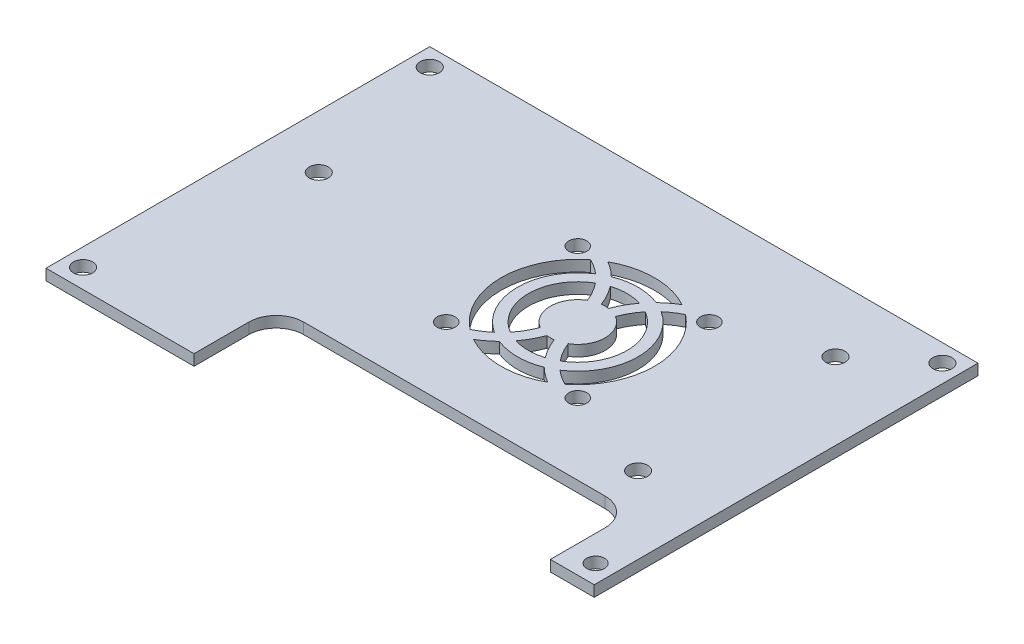
SolidWorks part; units mm, degrees
ref_plane "Front Plane" through (0, 0, 0) normal (0, 0, 1) x (1, 0, 0)
ref_plane "Top Plane" through (0, 0, 0) normal (0, 1, 0) x (1, 0, 0)
ref_plane "Right Plane" through (0, 0, 0) normal (1, 0, 0) x (0, 0, -1)
sketch "Sketch1" plane through (0, 0, 0) normal (0, 1, 0) x (1, 0, 0)
  line L0 (0, 35) -> (0, -35) construction
  line L1 (-50, 35) -> (50, 35)
  line L2 (-50, 35) -> (-50, -35)
  line L3 (-50, -35) -> (50, -35)
  line L4 (50, 35) -> (50, -35)
  line L5 (-46.75, -31.5) -> (46.75, -31.5) construction
  line L6 (7, 20) -> (7, -10) construction
  line L7 (-4, 20) -> (18, 20) construction
  line L8 (-8, 16) -> (-8, -6) construction
  line L9 (-4, -10) -> (18, -10) construction
  line L10 (22, 16) -> (22, -6) construction
  line L11 (-8, 5) -> (22, 5) construction
  circle A0 centre (-46.75, 31.75) radius 1.75
  circle A1 centre (46.75, 31.75) radius 1.75
  circle A2 centre (-46.75, -31.5) radius 1.75
  circle A3 centre (46.75, -31.5) radius 1.625
  arc A4 (-8, -6) -> (-4, -10) centre (-4, -6) ccw construction
  arc A5 (18, -10) -> (22, -6) centre (18, -6) ccw construction
  arc A6 (18, 20) -> (22, 16) centre (18, 16) cw construction
  arc A7 (-4, 20) -> (-8, 16) centre (-4, 16) ccw construction
  circle A12 centre (7, 5) radius 14
  circle A13 centre (-5, 17) radius 1.65
  circle A14 centre (-5, -7) radius 1.65
  circle A15 centre (19, -7) radius 1.65
  circle A16 centre (19, 17) radius 1.65
  point P4 (50, 0)
  point P5 (0, 35)
  point P17 (0, -31.5)
  dimension "D3" = 3.5
  dimension "D6" = 3.5
  dimension "D8" = 3.25
  dimension "D11" = 4
  dimension "D14" = 4
  dimension "D16" = 28
  dimension "D15" = 3.3
  dimension "D1" = 70
  dimension "D2" = 100
  dimension "D4" = 3.25
  dimension "D5" = 3.25
  dimension "D7" = 63.25
  dimension "D9" = 63.25
  dimension "D10" = 93.5
  dimension "D12" = 22
  dimension "D13" = 22
  dimension "D17" = 7
  dimension "D18" = 5
  dimension "D19" = 24
  dimension "D20" = 24
extrude "Boss-Extrude2" add sketch "Sketch1" along normal blind 2
sketch "Sketch2" plane through (0, 2, 0) normal (0, 1, 0) x (1, 0, 0)
  line L0 (-50, -35) -> (50, -35) construction
  line L1 (-18, -20) -> (37, -20)
  line L2 (-23, -25) -> (-23, -35)
  line L3 (-23, -35) -> (42, -35)
  line L4 (42, -25) -> (42, -35)
  line L5 (50, -35) -> (50, 35) construction
  arc A0 (37, -20) -> (42, -25) centre (37, -25) cw
  arc A1 (-18, -20) -> (-23, -25) centre (-18, -25) ccw
  point P12 (-23, -20)
  dimension "D4" = 5
  dimension "D1" = 15
  dimension "D2" = 8
  dimension "D3" = 65
extrude "Cut-Extrude1" cut sketch "Sketch2" against normal up to next
fillet "Fillet1" [suppressed] radius 2
sketch "Sketch3" plane through (0, 2, 0) normal (0, 1, 0) x (1, 0, 0)
  line L0 (7, 19) -> (7, -9) construction
  line L1 (7, 5) -> (-7, 5) construction
  circle A41 centre (7, 5) radius 14 construction
  arc A43 (0.2294, 17.2539) -> (0.2294, -7.2539) centre (-7, 5) cw
  arc A44 (-1.6603, 16) -> (-1.6603, -6) centre (-7, 5) cw
  circle A45 centre (7, 5) radius 11
  circle A46 centre (7, 5) radius 9
  circle A47 centre (7, 5) radius 5
  circle A48 centre (7, 5) radius 3.5
  arc A49 (15.6603, 16) -> (15.6603, -6) centre (21, 5) ccw
  arc A50 (13.7706, 17.2539) -> (13.7706, -7.2539) centre (21, 5) ccw
  point P9 (5.2275, 5)
  point P10 (7.2275, 5)
  circle M21 centre (7, 5) radius 14
  dimension "D1" = 22
  dimension "D2" = 2
  dimension "D3" = 2
  dimension "D4" = 1.5
  dimension "D5" = 22
  dimension "D6" = 10
extrude "Boss-Extrude5" add sketch "Sketch3" against normal blind 2 contours A45 A43 A44 M21 | A46 A43 A45 A44 | A47 A43 A46 A44 | A48 A43 A47 A44 | A43 A48 A44 | A48 A44 A47 A43 | A47 A44 A46 A43 | A46 A44 A45 A43 | A45 A44 A43 M21 | A48 A44 A47 | A46 A44 A45 | A48 A50 A49 | A50 A47 A43 A48 | A50 A45 A43 A46 | A45 A50 A46 A49 | A46 A50 A47 A49 | A47 A50 A48 A49 | A47 A49 A48 | A48 A50 A47 A49 | A50 A48 A43 A47 | A50 A46 A43 A45 | A46 A50 A45 A49 | A47 A50 A46 A49 | A45 A50 A49 M21 | A45 A49 A46 | A50 A45 A49 M21 | A43 A50
sketch "Sketch4" plane through (0, 2, 0) normal (0, 1, 0) x (1, 0, 0)
  line L0 (-17, 29) -> (-17, 13) construction
  line L1 (-16, 29) -> (-16, 13)
  line L2 (-18, 29) -> (-18, 13)
  line L3 (-5, 17) -> (-5, 29) construction
  line L4 (50, 35) -> (-50, 35) construction
  arc A0 (-16, 29) -> (-18, 29) centre (-17, 29) ccw
  arc A1 (-18, 13) -> (-16, 13) centre (-17, 13) ccw
  point P2 (-17, 21)
  dimension "D2" = 1
  dimension "D1" = 16
  dimension "D3" = 12
  dimension "D4" = 6
extrude "Cut-Extrude2" [suppressed] cut sketch "Sketch4" against normal up to next
sketch "Sketch5" [suppressed] plane through (0, 0, 0) normal (0, -1, 0) x (1, 0, 0)
  line L0 (-15, -13) -> (-15, -29) construction
  line L1 (-14, -13) -> (-14, -29)
  line L2 (-16, -13) -> (-16, -29)
  line L3 (-16, -29) -> (-16, -13) construction
  arc A0 (-14, -13) -> (-16, -13) centre (-15, -13) ccw
  arc A1 (-16, -29) -> (-14, -29) centre (-15, -29) ccw
  point P2 (-15, -21)
  point P10 (-16, -21)
  dimension "D1" = 1
  dimension "D2" = 16
extrude "Boss-Extrude6" [suppressed] add sketch "Sketch5" along normal blind 10
ref_plane "Plane1" [suppressed] through (-9, 0, 0) normal (1, 0, 0) x (0, 0, -1)
sketch "Sketch6" [suppressed] plane through (-9, 0, 0) normal (1, 0, 0) x (0, 0, -1)
  line L0 (13, -15) -> (29, -15) construction
  line L1 (13, -14) -> (29, -14)
  line L2 (13, -16) -> (29, -16)
  line L3 (29, -10) -> (13, -10) construction
  arc A0 (13, -14) -> (13, -16) centre (13, -15) ccw
  arc A1 (29, -16) -> (29, -14) centre (29, -15) ccw
  point P2 (21, -15)
  point P10 (21, -10)
  dimension "D1" = 1
  dimension "D2" = 16
  dimension "D3" = 5
ref_plane "Plane2" [suppressed] through (0, 0, -21) normal (0, 0, -1) x (-1, 0, 0)
sketch "Sketch10" [suppressed] plane through (0, 0, -21) normal (0, 0, -1) x (-1, 0, 0)
  line L0 (9, 5.5) -> (9, -5.5) construction
  line L1 (14, -10) -> (16, -10) construction
  arc A0 (9, -15) -> (15, -10) centre (9, -8.9) ccw
sweep "Sweep1" [suppressed] add profiles "Sketch6" path "Sketch10"
sketch "Sketch11" plane through (0, 2, 0) normal (0, 1, 0) x (1, 0, 0)
  line L0 (56, 5) -> (100, 5) construction
  line L1 (51.4545, 16.6443) -> (89.6364, 31.5489) construction
  line L2 (51.4545, -6.6443) -> (89.6364, -21.5489) construction
  line L3 (64, 23) -> (64, -13) construction
  line L5 (50, -35) -> (50, 35) construction
  line L6 (100, 5) -> (140.25, 5) construction
  line L7 (127.627, 12) -> (127.627, -2) construction
  line L8 (127.627, 12) -> (141.1254, 9.1589) construction
  line L9 (127.627, -2) -> (141.1254, 0.8411) construction
  line L10 (-27.627, -2) -> (-41.1254, 0.8411) construction
  line L11 (-27.627, 12) -> (-41.1254, 9.1589) construction
  line L12 (-27.627, 12) -> (-27.627, -2) construction
  line L13 (0, 5) -> (-40.25, 5) construction
  line L14 (36, 23) -> (36, -13) construction
  line L15 (48.5455, -6.6443) -> (10.3636, -21.5489) construction
  line L16 (48.5455, 16.6443) -> (10.3636, 31.5489) construction
  line L17 (44, 5) -> (0, 5) construction
  circle A0 centre (100, 5) radius 28.5 construction
  circle A1 centre (56, 5) radius 12.5 construction
  circle A2 centre (64, -13) radius 4.5 construction
  circle A3 centre (64, -13) radius 4.5 construction
  circle A4 centre (64, 23) radius 4.5 construction
  circle A5 centre (64, 23) radius 4.5 construction
  circle A6 centre (64, -13) radius 1.75 construction
  circle A7 centre (140.25, 5) radius 4.25 construction
  circle A9 centre (64, 23) radius 1.75 construction
  circle A10 centre (140.25, 5) radius 1.75 construction
  circle A11 centre (44, 5) radius 12.5 construction
  circle A12 centre (-40.25, 5) radius 1.75
  circle A13 centre (36, 23) radius 1.75
  circle A14 centre (-40.25, 5) radius 4.25 construction
  circle A15 centre (36, -13) radius 1.75
  circle A16 centre (36, 23) radius 4.5 construction
  circle A17 centre (36, 23) radius 4.5 construction
  circle A18 centre (36, -13) radius 4.5 construction
  circle A19 centre (36, -13) radius 4.5 construction
  circle A20 centre (0, 5) radius 28.5 construction
  point P16 (64, 5)
  point P17 (56, 5)
  point P28 (127.627, 5)
  point P32 (0, 0)
  point P56 (44, 5)
  dimension "D1" = 57
  dimension "D2" = 25
  dimension "D4" = 9
  dimension "D6" = 9
  dimension "D8" = 3.5
  dimension "D10" = 8.5
  dimension "D3" = 8
  dimension "D5" = 36
  dimension "D7" = 44
  dimension "D9" = 40.25
  dimension "D11" = 14
  dimension "D13" = 5
extrude "Cut-Extrude3" cut sketch "Sketch11" against normal through all
equation "\"D13@Sketch1\"=\"D12@Sketch1\""
equation "\"D20@Sketch1\"=\"D19@Sketch1\""
